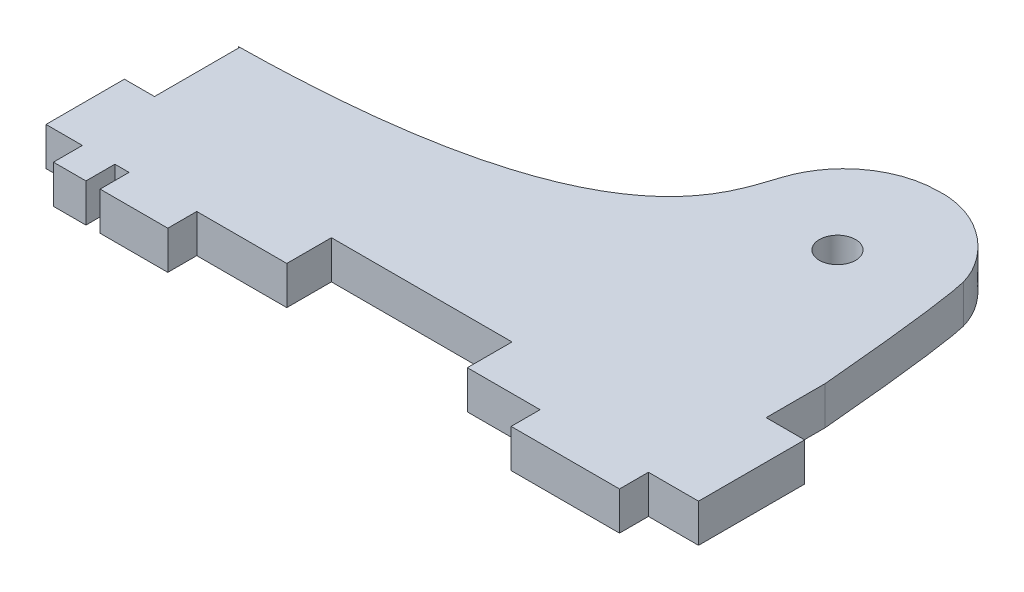
SolidWorks part; units mm, degrees
material "Acrylic (Medium-high impact)"
ref_plane "Front Plane" through (0, 0, 0) normal (0, 0, 1) x (1, 0, 0)
ref_plane "Top Plane" through (0, 0, 0) normal (0, 1, 0) x (1, 0, 0)
ref_plane "Right Plane" through (0, 0, 0) normal (1, 0, 0) x (0, 0, -1)
sketch "Sketch1" plane through (0, 0, 0) normal (0, 1, 0) x (1, 0, 0)
  line L0 (17.5838, 10.7432) -> (17.5836, 7.7433) construction
  line L8 (29.862, -5.7573) -> (26.6676, -5.7573)
  line L9 (26.6676, -5.7573) -> (26.6676, -0.8571)
  line L10 (-21.8462, -0.9895) -> (-21.7466, -0.9895)
  line L11 (-21.7466, -0.9895) -> (-21.7466, -8.0575)
  line L12 (-21.7466, -8.0575) -> (-24.2422, -8.0575)
  line L13 (-24.2422, -8.0575) -> (-24.2422, -14.5575)
  line L14 (-24.2422, -14.5575) -> (-21.2259, -14.5575)
  line L15 (-21.2259, -14.5575) -> (-21.2259, -16.9577)
  line L16 (-21.2259, -16.9577) -> (-18.5308, -16.9577)
  line L17 (-18.5308, -16.9577) -> (-18.5308, -14.5575)
  line L18 (-18.5308, -14.5575) -> (-17.3543, -14.5575)
  line L19 (-17.3543, -14.5575) -> (-17.3543, -16.9577)
  line L20 (-17.3543, -16.9577) -> (-11.7427, -16.9577)
  line L21 (-11.7427, -16.9577) -> (-11.7427, -14.5575)
  line L22 (-11.7427, -14.5575) -> (-4.2904, -14.5575)
  line L23 (-4.2904, -14.5575) -> (-4.2775, -14.5575)
  line L24 (-4.2775, -14.5575) -> (-4.2775, -10.8573)
  line L25 (-4.2775, -10.8573) -> (10.6959, -10.8573)
  line L26 (10.6959, -10.8573) -> (10.6959, -14.5574)
  line L27 (10.6959, -14.5574) -> (16.7243, -14.5574)
  line L28 (16.7243, -14.5574) -> (16.7243, -16.9577)
  line L29 (16.7243, -16.9577) -> (25.7085, -16.9577)
  line L30 (25.7085, -16.9577) -> (25.7085, -14.5575)
  line L31 (25.7085, -14.5575) -> (29.862, -14.5575)
  line L32 (29.862, -14.5575) -> (29.862, -5.7573)
  circle A0 centre (17.5837, 9.2432) radius 1.5
  spline S16 degree 3 poles (26.6676, -0.8571) (25.7236, 9.9229) (25.1036, 12.2574) (25.0952, 12.1681) knots 3 3 3 3 4 4 4 4
  spline S17 degree 3 poles (25.0952, 12.1681) (24.4673, 14.6329) (21.3273, 17.8433) (17.5836, 17.6473) knots 4 4 4 4 5 5 5 5
  spline S18 degree 3 poles (17.5836, 17.6473) (14.1128, 17.6473) (11.1652, 15.4016) (10.1099, 12.2819) knots 5 5 5 5 6 6 6 6
  spline S19 degree 3 poles (10.1099, 12.2819) (8.8752, 9.0993) (8.3536, -0.5846) (-21.8462, -0.9895) knots 6 6 6 6 7 7 7 7
  point P0 (17.5836, 9.2433)
extrude "Boss-Extrude1" add sketch "Sketch1" along normal blind 3.175
